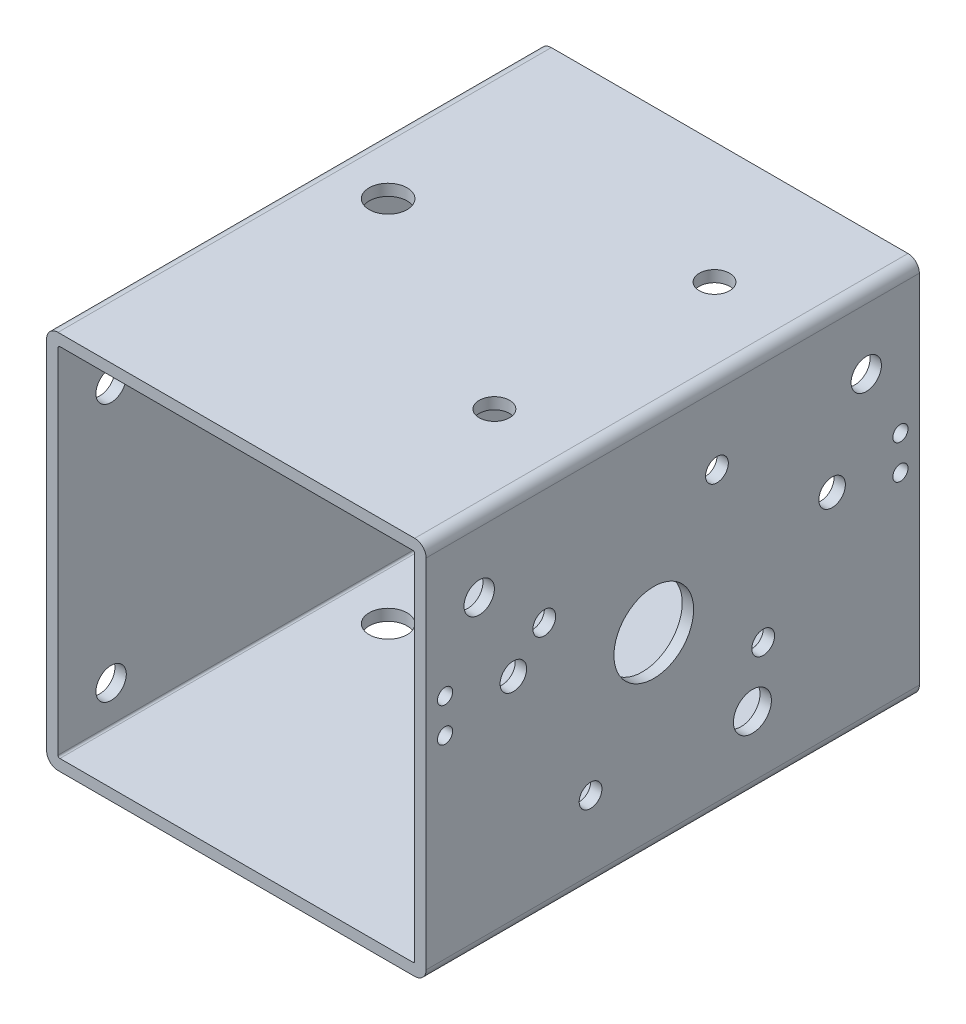
SolidWorks part; units mm, degrees
ref_plane "Front Plane" through (0, 0, 0) normal (0, 0, 1) x (1, 0, 0)
ref_plane "Top Plane" through (0, 0, 0) normal (0, 1, 0) x (1, 0, 0)
ref_plane "Right Plane" through (0, 0, 0) normal (1, 0, 0) x (0, 0, -1)
sketch "Sketch1" plane through (0, 0, 0) normal (0, 0, 1) x (1, 0, 0)
  line L1 (-50, 50) -> (50, 50)
  line L2 (-50, 50) -> (-50, -50)
  line L3 (-50, -50) -> (50, -50)
  line L4 (50, 50) -> (50, -50)
  line L5 (-50, 50) -> (50, -50) construction
  line L6 (-50, -50) -> (50, 50) construction
  point P0 (0, 0)
  dimension "D1" = 100
  dimension "D2" = 100
extrude "Extrude-Thin1" add sketch "Sketch1" along normal blind 130 thin
fillet "Fillet1" radius 0.5 4 edges at (-47, -47, 65) (-47, 47, 65) (47, 47, 65) (47, -47, 65)
fillet "Fillet2" radius 3 4 edges at (50, -50, 65) (-50, -50, 65) (50, 50, 65) (-50, 50, 65)
sketch "Holes - top" plane through (0, 0, 0) normal (0, 1, 0) x (1, 0, 0)
  line L0 (-3, 0) -> (-3, -130) construction
  line L1 (47, -130) -> (-47, -130) construction
  line L2 (-23, 0) -> (-23, -130) construction
  line L3 (47, 0) -> (-47, 0) construction
  line L4 (17, 0) -> (17, -130) construction
  circle A0 centre (-34, -56) radius 11 construction
  circle A1 centre (28, -90) radius 11 construction
  circle A2 centre (28, -32) radius 11 construction
  dimension "D4" = 22
  dimension "D1" = 40
  dimension "D2" = 40
  dimension "D3" = 32
  dimension "D5" = 56
  dimension "D6" = 3
hole_wizard "Ø8.0 (8) Diameter Hole2" positions "Sketch6" profile "Sketch5" hole size "Ø8.0" standard "ANSI Metric" end condition through all
sketch "Sketch6" plane through (0, 50, 0) normal (0, 1, 0) x (1, 0, 0)
  point P0 (28, -32)
  point P6 (28, -90)
sketch "Sketch5" plane through (28, 50, 32) normal (1, 0, 0) x (0, 0, 1)
  line L0 (0, 0) -> (0, 100)
  line L1 (0, 100) -> (4, 100)
  line L2 (4, 100) -> (4, 0)
  line L5 (4, 0) -> (0, 0)
  line L11 (0, -6.35) -> (0, 107.95) construction
  dimension "Thru Hole Dia." = 8
  dimension "Thru Hole Depth" = 100
sketch "Holes - side" plane through (0, 0, 0) normal (1, 0, 0) x (0, 0, -1)
  line L0 (0, 0) -> (-130, 0) construction
  line L1 (-130, -47) -> (-130, 47) construction
  line L2 (-130, 20) -> (0, 20) construction
  line L3 (0, -47) -> (0, 47) construction
  line L4 (-130, -20) -> (0, -20) construction
  circle A0 centre (-116, 31) radius 11 construction
  circle A1 centre (-14, 31) radius 11 construction
  circle A2 centre (-44, -31) radius 11 construction
  dimension "D1" = 40
  dimension "D2" = 22
  dimension "D3" = 14
  dimension "D4" = 14
  dimension "D5" = 44
hole_wizard "Ø8.0 (8) Diameter Hole3" positions "Sketch9" profile "Sketch8" hole size "Ø8.0" standard "ANSI Metric" end condition through all
sketch "Sketch9" plane through (50, 0, 0) normal (1, 0, 0) x (0, 0, -1)
  point P0 (-14, 31)
  point P3 (-116, 31)
sketch "Sketch8" plane through (50, 31, 14) normal (0, 1, 0) x (0, 0, -1)
  line L0 (0, 0) -> (0, 100)
  line L1 (0, 100) -> (4, 100)
  line L2 (4, 100) -> (4, 0)
  line L5 (4, 0) -> (0, 0)
  line L11 (0, -6.35) -> (0, 107.95) construction
  dimension "Thru Hole Dia." = 8
  dimension "Thru Hole Depth" = 100
hole_wizard "Ø10.0 (10) Diameter Hole1" positions "Sketch12" profile "Sketch11" hole size "Ø10.0" standard "ANSI Metric" end condition through all
sketch "Sketch12" plane through (0, 50, 0) normal (0, 1, 0) x (1, 0, 0)
  point P0 (-34, -56)
sketch "Sketch11" plane through (-34, 50, 56) normal (1, 0, 0) x (0, 0, 1)
  line L0 (0, 0) -> (0, 100)
  line L1 (0, 100) -> (5, 100)
  line L2 (5, 100) -> (5, 0)
  line L5 (5, 0) -> (0, 0)
  line L11 (0, -6.35) -> (0, 107.95) construction
  dimension "Thru Hole Dia." = 10
  dimension "Thru Hole Depth" = 100
hole_wizard "Ø10.0 (10) Diameter Hole2" positions "Sketch14" profile "Sketch13" hole size "Ø10.0" standard "ANSI Metric" end condition through all
sketch "Sketch14" plane through (50, 0, 0) normal (1, 0, 0) x (0, 0, -1)
  point P0 (-44, -31)
sketch "Sketch13" plane through (50, -31, 44) normal (0, 1, 0) x (0, 0, -1)
  line L0 (0, 0) -> (0, 100)
  line L1 (0, 100) -> (5, 100)
  line L2 (5, 100) -> (5, 0)
  line L5 (5, 0) -> (0, 0)
  line L11 (0, -6.35) -> (0, 107.95) construction
  dimension "Thru Hole Dia." = 10
  dimension "Thru Hole Depth" = 100
hole_wizard "M8 Tapped Hole1" positions "Sketch18" profile "Sketch17" tap size "M8" standard "ISO"
sketch "Sketch18" plane through (-50, 0, 0) normal (-1, 0, 0) x (0, 0, 1)
  line L0 (56, 35) -> (56, -15) construction
  point P0 (56, -15)
  point P2 (56, 35)
  dimension "D1" = 56
  dimension "D2" = 35
  dimension "D3" = 15
sketch "Sketch17" plane through (-50, -15, 56) normal (0, 1, 0) x (0, 0, 1)
  line L0 (0, 0) -> (0, 3)
  line L1 (0, 3) -> (3.4, 3)
  line L2 (3.4, 3) -> (3.4, 0)
  line L5 (3.4, 0) -> (0, 0)
  line L11 (0, -6.35) -> (0, 107.95) construction
  dimension "Thru Tap Drill Dia." = 6.8
  dimension "Thru Tap Drill Depth" = 3
cosmetic thread "Hole Thread1" parameters "D2"=8
cosmetic thread "Hole Thread2" parameters "D2"=8
hole_wizard "M8 Tapped Hole2" positions "Sketch21" profile "Sketch20" tap size "M8" standard "ISO"
sketch "Sketch21" plane through (0, -50, 0) normal (0, -1, 0) x (-1, 0, 0)
  line L0 (20, -44) -> (-35, -44) construction
  point P0 (20, -44)
  point P2 (-35, -44)
  dimension "D1" = 44
  dimension "D2" = 35
  dimension "D3" = 20
sketch "Sketch20" plane through (-20, -50, 44) normal (1, 0, 0) x (0, 0, -1)
  line L0 (0, 0) -> (0, 3)
  line L1 (0, 3) -> (3.4, 3)
  line L2 (3.4, 3) -> (3.4, 0)
  line L5 (3.4, 0) -> (0, 0)
  line L11 (0, -6.35) -> (0, 107.95) construction
  dimension "Thru Tap Drill Dia." = 6.8
  dimension "Thru Tap Drill Depth" = 3
cosmetic thread "Hole Thread3" parameters "D2"=8
cosmetic thread "Hole Thread4" parameters "D2"=8
sketch "Holes - Nema 23 motor" plane through (0, 0, 0) normal (1, 0, 0) x (0, 0, -1)
  line L0 (-98.8427, 16.6524) -> (-53.3476, 28.8427) construction
  line L1 (-98.8427, 16.6524) -> (-86.6524, -28.8427) construction
  line L2 (-53.3476, 28.8427) -> (-41.1573, -16.6524) construction
  line L3 (-86.6524, -28.8427) -> (-41.1573, -16.6524) construction
  line L4 (-98.8427, 16.6524) -> (-41.1573, -16.6524) construction
  line L5 (-53.3476, 28.8427) -> (-86.6524, -28.8427) construction
  line L6 (0, 0) -> (-130, 0) construction
  point P1 (-70, 0)
  dimension "D1" = 70
  dimension "D2" = 47.1
  dimension "D3" = 47.1
  dimension "D4" = 15
hole_wizard "Ø21.0 (21) Diameter Hole1" positions "Sketch24" profile "Sketch23" hole size "Ø21.0" standard "ANSI Metric"
sketch "Sketch24" plane through (50, 0, 0) normal (1, 0, 0) x (0, 0, -1)
  point P0 (-70, 0)
sketch "Sketch23" plane through (50, 0, 70) normal (0, 1, 0) x (0, 0, -1)
  line L0 (0, 0) -> (0, 3)
  line L1 (0, 3) -> (10.5, 3)
  line L2 (10.5, 3) -> (10.5, 0)
  line L5 (10.5, 0) -> (0, 0)
  line L11 (0, -6.35) -> (0, 107.95) construction
  dimension "Thru Hole Dia." = 21
  dimension "Thru Hole Depth" = 3
hole_wizard "Ø6.0 (6) Diameter Hole1" positions "Sketch26" profile "Sketch25" hole size "Ø6.0" standard "ANSI Metric"
sketch "Sketch26" plane through (50, 0, 0) normal (1, 0, 0) x (0, 0, -1)
  point P0 (-41.1573, -16.6524)
  point P3 (-53.3476, 28.8427)
  point P6 (-98.8427, 16.6524)
  point P9 (-86.6524, -28.8427)
sketch "Sketch25" plane through (50, -16.6524, 41.1573) normal (0, 1, 0) x (0, 0, -1)
  line L0 (0, 0) -> (0, 3)
  line L1 (0, 3) -> (3, 3)
  line L2 (3, 3) -> (3, 0)
  line L5 (3, 0) -> (0, 0)
  line L11 (0, -6.35) -> (0, 107.95) construction
  dimension "Thru Hole Dia." = 6
  dimension "Thru Hole Depth" = 3
sketch "Sketch27" plane through (50, 0, 0) normal (1, 0, 0) x (0, 0, -1)
  line L1 (0, -47) -> (0, 47) construction
  line L2 (-130, 50) -> (0, 50) construction
  line L3 (-65, 66.9997) -> (-65, -40.3101) construction
  line L4 (-130, -47) -> (-130, 47) construction
  circle A0 centre (-5, 13) radius 2
  circle A1 centre (-5, 4) radius 2
  circle A2 centre (-23, 8.5) radius 3.5
  circle A3 centre (-107, 8.5) radius 3.5
  circle A4 centre (-125, 4) radius 2
  circle A5 centre (-125, 13) radius 2
  dimension "D1" = 4
  dimension "D2" = 9
  dimension "D3" = 5
  dimension "D4" = 46
  dimension "D7" = 18
  dimension "D8" = 4.5
  dimension "D9" = 7
  dimension "D5" = 0
  dimension "D6" = 65
extrude "Cut-Extrude1" cut sketch "Sketch27" against normal up to next
sketch "Sketch31" plane through (-50, 0, 0) normal (-1, 0, 0) x (0, 0, 1)
  line L0 (0, 47) -> (0, -47) construction
  line L1 (130, 47) -> (130, -47) construction
  line L2 (0, -47) -> (130, -47) construction
  circle A0 centre (14, -37) radius 4
  circle A1 centre (116, -37) radius 4
  dimension "D1" = 8
  dimension "D2" = 8
  dimension "D3" = 14
  dimension "D4" = 14
  dimension "D5" = 10
extrude "Cut-Extrude2" cut sketch "Sketch31" against normal up to next
equation "\"L\"= 130"
equation "\"D1@Extrude-Thin1\"=\"L\""
equation "\"d-bearing\"= 22'diameter of bearing"
equation "\"D4@Holes - top\"=\"d-bearing\""
equation "\"D2@Holes - side\"=\"d-bearing\""
